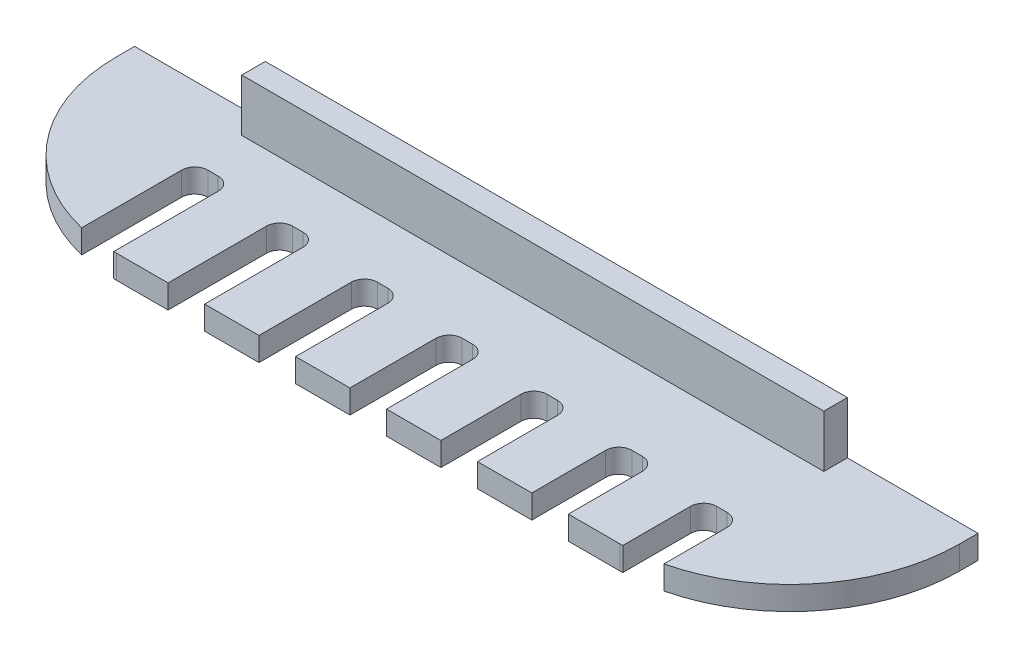
SolidWorks part; units mm, degrees
ref_plane "Front Plane" through (0, 0, 0) normal (0, 0, 1) x (1, 0, 0)
ref_plane "Top Plane" through (0, 0, 0) normal (0, 1, 0) x (1, 0, 0)
ref_plane "Right Plane" through (0, 0, 0) normal (1, 0, 0) x (0, 0, -1)
sketch "Sketch2" plane through (0, 0, 0) normal (0, 1, 0) x (1, 0, 0)
  line L0 (-32.275, 7.2) -> (-22.275, 7.2) construction
  line L1 (-32.275, 7.2) -> (32.275, 7.2)
  line L2 (32.275, 7.2) -> (32.275, 5.8)
  line L3 (19.275, -7.2) -> (15.325, -7.2)
  line L4 (-32.275, 5.8) -> (-32.275, 7.2)
  line L5 (22.285, -2.0121) -> (22.285, -6.8467)
  line L6 (-15.315, -7.2) -> (-19.275, -7.2)
  line L7 (-8.355, -7.2) -> (-12.515, -7.2)
  line L9 (-22.275, 0.8) -> (-22.275, -6.8491)
  line L10 (-21.275, 1.8) -> (-20.475, 1.8)
  line L13 (-19.475, 0.8) -> (-19.475, -7.1985)
  line L14 (-12.515, 0.3313) -> (-12.515, -7.2)
  line L16 (-15.315, 0.3313) -> (-15.315, -7.2)
  line L18 (-5.555, -0.1374) -> (-5.555, -7.2)
  line L20 (-8.355, -0.1374) -> (-8.355, -7.2)
  line L22 (1.405, -0.6061) -> (1.405, -7.2)
  line L24 (-1.395, -0.6061) -> (-1.395, -7.2)
  line L26 (8.365, -1.0747) -> (8.365, -7.2)
  line L28 (5.565, -1.0747) -> (5.565, -7.2)
  line L30 (15.325, -1.5434) -> (15.325, -7.2)
  line L32 (12.525, -1.5434) -> (12.525, -7.2)
  line L36 (19.485, -2.0121) -> (19.485, -7.1983)
  line L37 (-14.315, 1.3313) -> (-13.515, 1.3313)
  line L38 (-7.355, 0.8626) -> (-6.555, 0.8626)
  line L39 (-0.395, 0.3939) -> (0.405, 0.3939)
  line L40 (6.565, -0.0747) -> (7.365, -0.0747)
  line L41 (13.525, -0.5434) -> (14.325, -0.5434)
  line L42 (20.485, -1.0121) -> (21.285, -1.0121)
  line L43 (-1.395, -7.2) -> (-5.555, -7.2)
  line L44 (-15.315, 1.8) -> (-12.515, 1.8) [skipped]
  line L45 (-8.355, 1.8) -> (-5.555, 1.8) [skipped]
  line L46 (-1.395, 1.8) -> (0, 1.8) [skipped]
  line L47 (5.565, 1.8) -> (8.365, 1.8) [skipped]
  line L48 (12.525, 1.8) -> (15.325, 1.8) [skipped]
  line L49 (19.485, 1.8) -> (22.285, 1.8) [skipped]
  line L54 (22.285, -1.0121) -> (22.285, -6.8467) [skipped]
  line L55 (5.565, -7.2) -> (1.405, -7.2)
  line L56 (12.525, -7.2) -> (8.365, -7.2)
  arc A0 (-19.275, -7.2) -> (-19.475, -7.1985) centre (-19.275, 5.8) cw
  arc A1 (19.275, -7.2) -> (19.485, -7.1983) centre (19.275, 5.8) ccw
  arc A2 (-22.275, -6.8491) -> (-32.275, 5.8) centre (-19.275, 5.8) cw
  arc A3 (22.285, -6.8467) -> (32.275, 5.8) centre (19.275, 5.8) ccw
  arc A4 (21.285, -1.0121) -> (22.285, -2.0121) centre (21.285, -2.0121) cw
  arc A5 (20.485, -1.0121) -> (19.485, -2.0121) centre (20.485, -2.0121) ccw
  arc A6 (15.325, -1.5434) -> (14.325, -0.5434) centre (14.325, -1.5434) ccw
  arc A7 (12.525, -1.5434) -> (13.525, -0.5434) centre (13.525, -1.5434) cw
  arc A8 (7.365, -0.0747) -> (8.365, -1.0747) centre (7.365, -1.0747) cw
  arc A9 (6.565, -0.0747) -> (5.565, -1.0747) centre (6.565, -1.0747) ccw
  arc A10 (0.405, 0.3939) -> (1.405, -0.6061) centre (0.405, -0.6061) cw
  arc A11 (-1.395, -0.6061) -> (-0.395, 0.3939) centre (-0.395, -0.6061) cw
  arc A12 (-6.555, 0.8626) -> (-5.555, -0.1374) centre (-6.555, -0.1374) cw
  arc A13 (-8.355, -0.1374) -> (-7.355, 0.8626) centre (-7.355, -0.1374) cw
  arc A14 (-13.515, 1.3313) -> (-12.515, 0.3313) centre (-13.515, 0.3313) cw
  arc A15 (-15.315, 0.3313) -> (-14.315, 1.3313) centre (-14.315, 0.3313) cw
  arc A16 (-19.475, 0.8) -> (-20.475, 1.8) centre (-20.475, 0.8) ccw
  arc A17 (-22.275, 0.8) -> (-21.275, 1.8) centre (-21.275, 0.8) cw
  point P4 (0, 0)
  point P7 (0, 7.2)
  dimension "D3" = 13
  dimension "D1" = 1
  dimension "D2" = 64.55
  dimension "D4" = 7
extrude "Boss-Extrude1" add sketch "Sketch2" along normal blind 1.8
sketch "Sketch4" plane through (0, 1.8, 0) normal (0, 1, 0) x (1, 0, 0)
  line L0 (-32.275, 7.2) -> (-22.275, 7.2) construction
  line L1 (32.275, 7.2) -> (-32.275, 7.2) construction
  line L2 (-22.275, 7.2) -> (22.275, 7.2)
  line L4 (-22.275, 7.2) -> (-22.275, 5.4)
  line L5 (-22.275, 5.4) -> (22.275, 5.4)
  line L6 (22.275, 7.2) -> (22.275, 5.4)
extrude "Boss-Extrude2" add sketch "Sketch4" along normal blind 4
